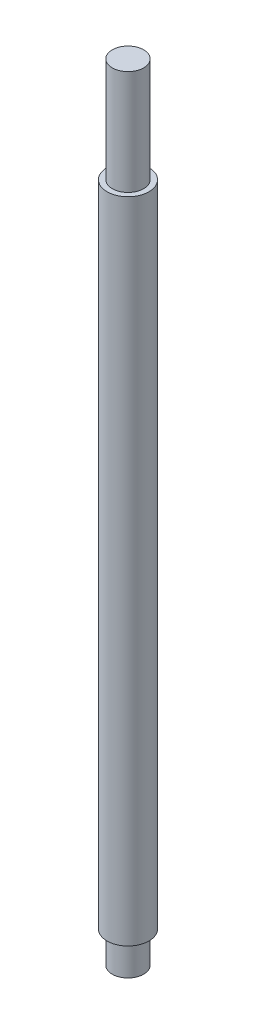
SolidWorks part; units mm, degrees
material "Polyetheretherketone (PEEK)"
ref_plane "Front Plane" through (0, 0, 0) normal (0, 0, 1) x (1, 0, 0)
ref_plane "Top Plane" through (0, 0, 0) normal (0, 1, 0) x (1, 0, 0)
ref_plane "Right Plane" through (0, 0, 0) normal (1, 0, 0) x (0, 0, -1)
sketch "Sketch1" plane through (0, 0, 0) normal (0, 1, 0) x (1, 0, 0)
  circle A0 centre (0, 0) radius 2
  dimension "D1" = 4
extrude "Boss-Extrude1" add sketch "Sketch1" along normal blind 62
sketch "Sketch2" plane through (0, 62, 0) normal (0, 1, 0) x (1, 0, 0)
  circle A0 centre (0, 0) radius 1.5
  dimension "D1" = 3
extrude "Boss-Extrude2" add sketch "Sketch2" along normal blind 10
sketch "Sketch3" plane through (0, 0, 0) normal (0, -1, 0) x (1, 0, 0)
  circle A0 centre (0, 0) radius 1.5
  dimension "D1" = 3
extrude "Boss-Extrude3" add sketch "Sketch3" along normal blind 3
